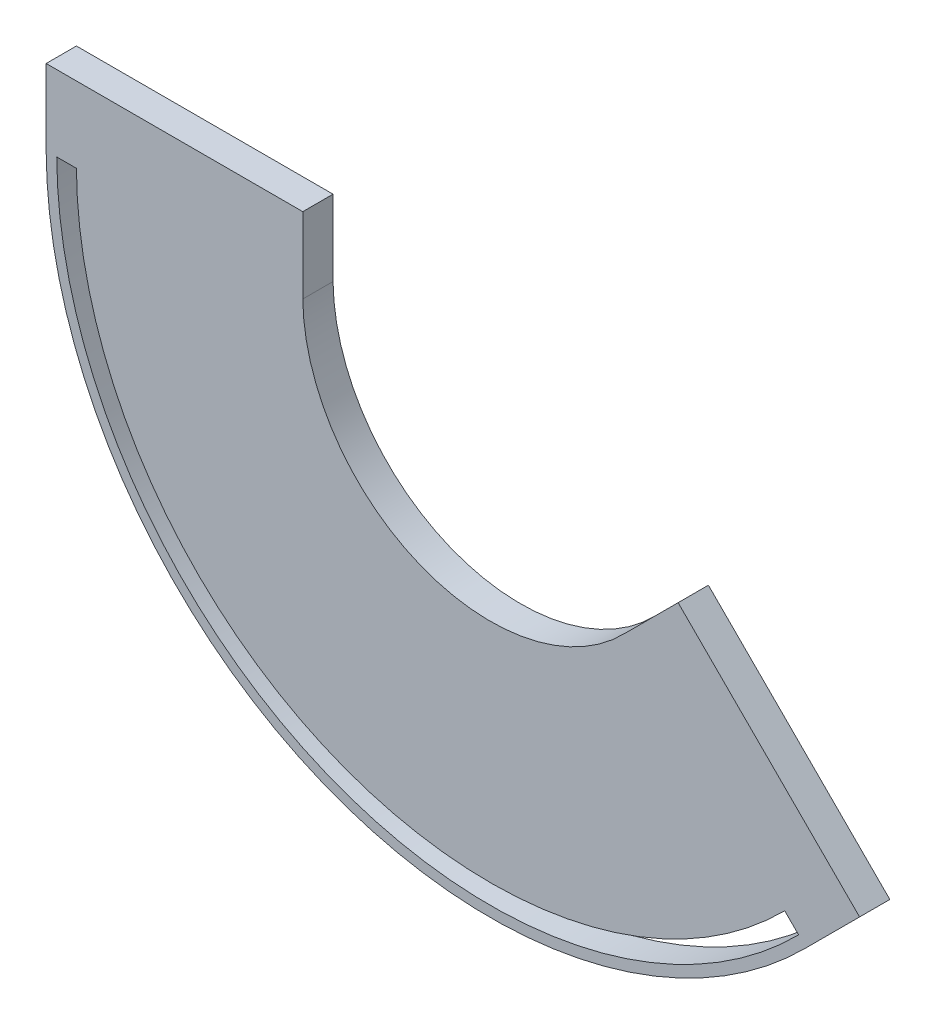
SolidWorks part; units mm, degrees
ref_plane "Front Plane" through (0, 0, 0) normal (0, 0, 1) x (1, 0, 0)
ref_plane "Top Plane" through (0, 0, 0) normal (0, 1, 0) x (1, 0, 0)
ref_plane "Right Plane" through (0, 0, 0) normal (1, 0, 0) x (0, 0, -1)
sketch "Sketch2" plane through (0, 0, 0) normal (0, 0, 1) x (1, 0, 0)
  line L0 (22.5377, -22.0011) -> (53.0008, -52.4642) construction
  line L1 (-74.575, -0.3794) -> (-31.4937, -0.3794) construction
  line L2 (22.5377, -22.0011) -> (31.518, -13.0209)
  line L3 (31.518, -13.0209) -> (61.9811, -43.484)
  line L4 (53.0008, -52.4642) -> (61.9811, -43.484)
  line L6 (-74.575, -0.3794) -> (-31.4937, -0.3794) construction
  line L7 (-74.575, -0.3794) -> (-74.575, 12.3206)
  line L8 (-74.575, 12.3206) -> (-31.4937, 12.3206)
  line L9 (-31.4937, -0.3794) -> (-31.4937, 12.3206)
  arc A0 (-31.4937, -0.3794) -> (22.5377, -22.0011) centre (0, 0) ccw
  arc A1 (-74.575, -0.3794) -> (53.0008, -52.4642) centre (0, 0) ccw
  dimension "D2" = 74.576
  dimension "D1" = 31.496
  dimension "D3" = 12.7
  dimension "D4" = 12.7
extrude "Boss-Extrude3" add sketch "Sketch2" along normal blind 5.08
sketch "Sketch3" plane through (0, 0, 5.08) normal (0, 0, 1) x (1, 0, 0)
  line L0 (-31.4937, -0.3794) -> (-74.575, -0.3794) construction
  line L1 (53.0008, -52.4642) -> (22.5377, -22.0011) construction
  line L2 (53.0008, -52.4642) -> (61.9811, -43.484) construction
  line L3 (-72.797, -0.3794) -> (-69.495, -0.3794)
  line L4 (49.4087, -48.8721) -> (51.7436, -51.207)
  arc A0 (-74.575, -0.3794) -> (53.0008, -52.4642) centre (0, 0) ccw construction
  arc A1 (-69.495, -0.3794) -> (49.4087, -48.8721) centre (0, 0) ccw
  arc A2 (-72.797, -0.3794) -> (51.7436, -51.207) centre (0, 0) ccw
  dimension "D1" = 69.496
  dimension "D2" = 72.798
extrude "Cut-Extrude1" cut sketch "Sketch3" against normal through all
equation "\"FoamCore\" = \".2\""
equation "\"MDF\" = \".2\""
equation "\"GMaterial\"= \".2\""
equation "\"PVCMountDiameter\" = \"0.5in\""
equation "\"PVCMountDistanceToEdge\" = \"0.5\""
equation "\"PVCThickness\" = \"0.13in\""
equation "\"PVCDiameter\" = 1.5in"
equation "\"BaseWidth\" = \"8in\""
equation "\"BaseLength\" = \"10in\""
equation "\"BallDiameter\" = \"38mm\""
equation "\"BaseGap\" = \"4in\""
equation "\"FunnelTopDiameter\" = \"8in\""
equation "\"FunnelTopDepth\" = \"0.5in\""
equation "\"BallGap\" = \"0.1in\""
equation "\"FunnelLength\" = 3in"
equation "\"FunnelMaterial\" = 0.1in"
equation "\"FunnelLowerDiameter\" = 1.9in"
equation "\"FunnelDepth\" = 1.5in"
equation "\"FunnelBendLength\" = 2*pi*\"FunnelLowerDiameter\"/2*135"
equation "\"AmmoFeederLength\" = 1.5in + 76mm"
equation "\"WheelThickness\" = 0.5in"
equation "\"LauncherWheelDiameter\" = 76mm"
equation "\"MotorFrontLength\" = 0.95in"
equation "\"MotorBodyTotalLength\" = 2.03in"
equation "\"MotorFrontDiameter\" = 1.5in"
equation "\"MotorLowerDriveshaftDiameter\" = 0.46in"
equation "\"MotorLowerDriveshaftThickness\" = 0.25in"
equation "\"MotorFullDriveshaftLength\" = 0.78in"
equation "\"MotorDriveshaftDiameter\" = 0.23in"
equation "\"MotorDriveshaftFlatThickness\" = 0.2in"
equation "\"MotorRearDiameter\" = 31.9mm"
equation "\"MotorDriveshaftBottomToTop\" = 31.1mm"
equation "\"MotorFlatDriveshaftLength\" = 11.7mm"
equation "\"MotorDistanceBetweenLowerandTopHoles\" = 0.5in"
equation "\"MotorMountsDistanceFromEdge\" = 0.06in"
equation "\"MotorScrewMountDiameter\" = 0.1in"
equation "\"MotorScrewMountDepth\" = 0.13in"
equation "\"HBRidgeScrewHoleDeep\" = 0.18in"
equation "\"MotorMountWidth\" = \"1.61in\""
equation "\"MotorMountLength\" = \"1.58in\""
equation "\"MotorMountToEdgeGap\" = \"3.3mm\""
equation "\"MotorMountToInsideEdgeGap\" = \"6.5mm\""
equation "\"MotorMountToMountWidthGap\" = \"25.8mm\""
equation "\"MotorMountToMountLengthGap\" = \"20.5mm\""
equation "\"MotorMountMaterialThickness\" = 1.6mm"
equation "\"MotorMountBaseScrewholeDiameter\" = 3.8mm"
equation "\"MotorMountBaseDistancebetweenHoles\" = 0.8in"
equation "\"MotorMountHeight\" = 1.85in"
equation "\"HBridgeWidth\" = 2.25in"
equation "\"HBridgeLength\" = 1.40in"
equation "\"UnoWidth\" = 3.13in"
equation "\"UnoLength\" = 3.06in"
equation "\"BatteryWidth\" = 1.15in"
equation "\"BatteryLength\" = 3.86in"
equation "\"ScrewDiameter\" = 2.7mm"
equation "\"MotorMountFaceScrewtoBase\" = 0.46in"
equation "\"MotorMountFaceDistanceBetweenScrews\" = 0.95in"
equation "\"MotorMountFaceMiddletoEdge\" = 0.16in"
equation "\"MotorMountFaceBottomtoEdge\" = 0.42in"
equation "\"MotorMountCenterholeHeight\" = 1.04in"
equation "\"MotorMountCenterholetoEdge\" = 0.25in"
equation "\"MovingWheelDiameter\" = 76mm"
equation "\"MovingWheelThickness\" = 0.5in"
equation "\"BraceLength\" = 1in"
equation "\"BraceVerticalOffset\" = 3.5in"
equation "\"BraceHorizontalOffset\" = 2.5in"
equation "\"BaseToBaseDistance\" = 3.6in"
equation "\"PVCOutsideDiameter\" = \"PVCDiameter\" + 2*\"PVCThickness\""
equation "\"Distancebetweenwalls\" = 6in"
equation "\"Slidewidth\" = 0.3in"
equation "\"Slidelength\" = 0.8in"
equation "\"Bottomtofloor\" = 0.53in"
equation "\"tabdistance\" = 0.2in"
equation "\"tabwidth\" = 0.3in"
equation "\"ShooterWheelDiameter\"= 1.88in"
equation "\"ShooterWheelThick\"= 1.03in"
equation "\"ShooterRubberThick\"= 0.3in"
equation "\"3DMaterial\" = \"PVCThickness\""
equation "\"D2@Sketch2\"= (\"ShooterWheelDiameter\"/2) + \"ShooterRubberThick\"+ \"BallDiameter\"+\"MDF\""
equation "\"D1@Sketch2\"=(\"ShooterWheelDiameter\"/2) + \"ShooterRubberThick\""
equation "\"D3@Sketch2\"=0.5"
equation "\"D1@Boss-Extrude3\"=\"MDF\""
equation "\"D1@Sketch3\"=(\"ShooterWheelDiameter\"/2) + \"ShooterRubberThick\" + \"BallDiameter\""
equation "\"D2@Sketch3\"=(\"ShooterWheelDiameter\"/2) + \"ShooterRubberThick\" + \"BallDiameter\" + \"3DMaterial\""
